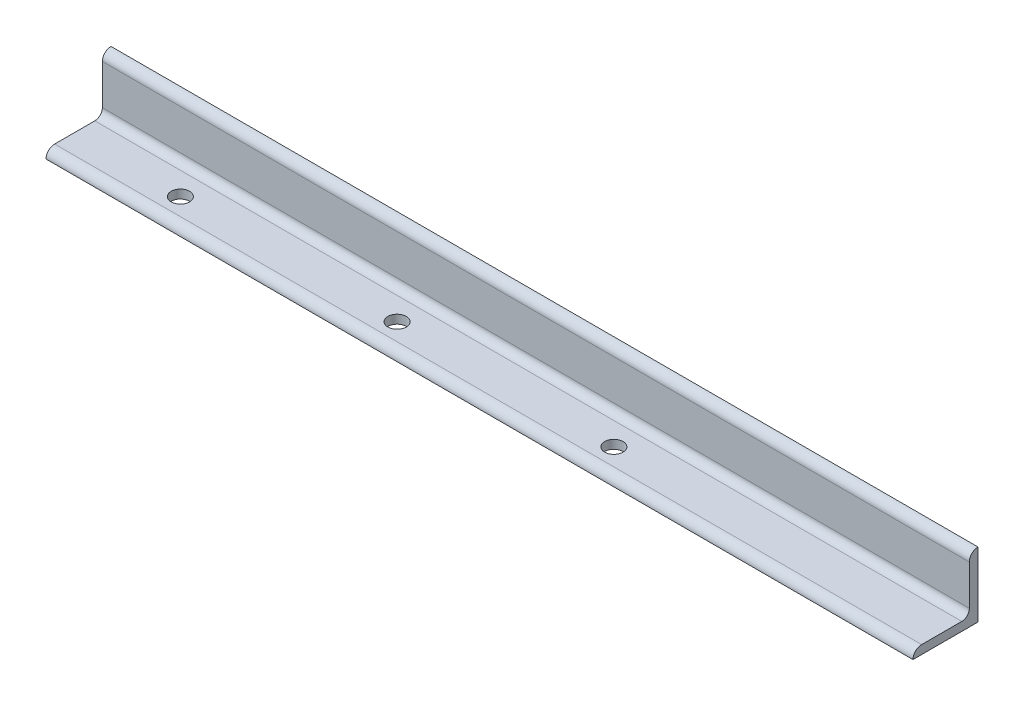
SolidWorks part; units mm, degrees
ref_plane "Front Plane" through (0, 0, 0) normal (0, 0, 1) x (1, 0, 0)
ref_plane "Top Plane" through (0, 0, 0) normal (0, 1, 0) x (1, 0, 0)
ref_plane "Right Plane" through (0, 0, 0) normal (1, 0, 0) x (0, 0, -1)
sketch "Sketch1" plane through (0, 0, 0) normal (0, 0, 1) x (1, 0, 0)
  line L0 (0, 0) -> (400, 0)
  dimension "D1" = 400
other "Angle iron 25 X 25 X 4(1)"
ref_plane "Plane1" through (0, 0, 0) normal (1, 0, 0) x (0, 1, 0)
sketch "Sketch11" plane through (0, 0, 0) normal (1, 0, 0) x (0, 1, 0)
  line L0 (0, 0) -> (0, 30)
  line L1 (0, 15) -> (4, 15) construction
  line L2 (4, 26) -> (4, 7.5)
  line L3 (7.5, 4) -> (26, 4)
  line L4 (15, 4) -> (15, 0) construction
  line L5 (30, 0) -> (0, 0)
  arc A0 (30, 0) -> (26, 4) centre (26, 0) ccw
  arc A1 (0, 30) -> (4, 26) centre (0, 26) cw
  arc A2 (7.5, 4) -> (4, 7.5) centre (7.5, 7.5) cw
  point P10 (15, 0)
  point P14 (0, 15)
  point P15 (4, 15)
  point P16 (15, 4)
  point P17 (4, 30)
  point P18 (30, 4)
  point P21 (0, 0)
  dimension "D2" = 4
  dimension "D3" = 30
  dimension "Radius_1" = 3.5
  dimension "D1" = 4
sketch "Sketch12" plane through (0, 4, 0) normal (0, 1, 0) x (1, 0, 0)
  line L0 (300, -18) -> (0, -18) construction
  line L3 (400, -30) -> (0, -30) construction
  circle A0 centre (50, -18) radius 4.25
  circle A1 centre (150, -18) radius 4.25
  circle A2 centre (250, -18) radius 4.25
  dimension "D1" = 8.5
  dimension "D2" = 12
  dimension "D3" = 150
  dimension "D4" = 100
  dimension "D5" = 100
extrude "Cut-Extrude1" cut sketch "Sketch12" against normal blind 10
